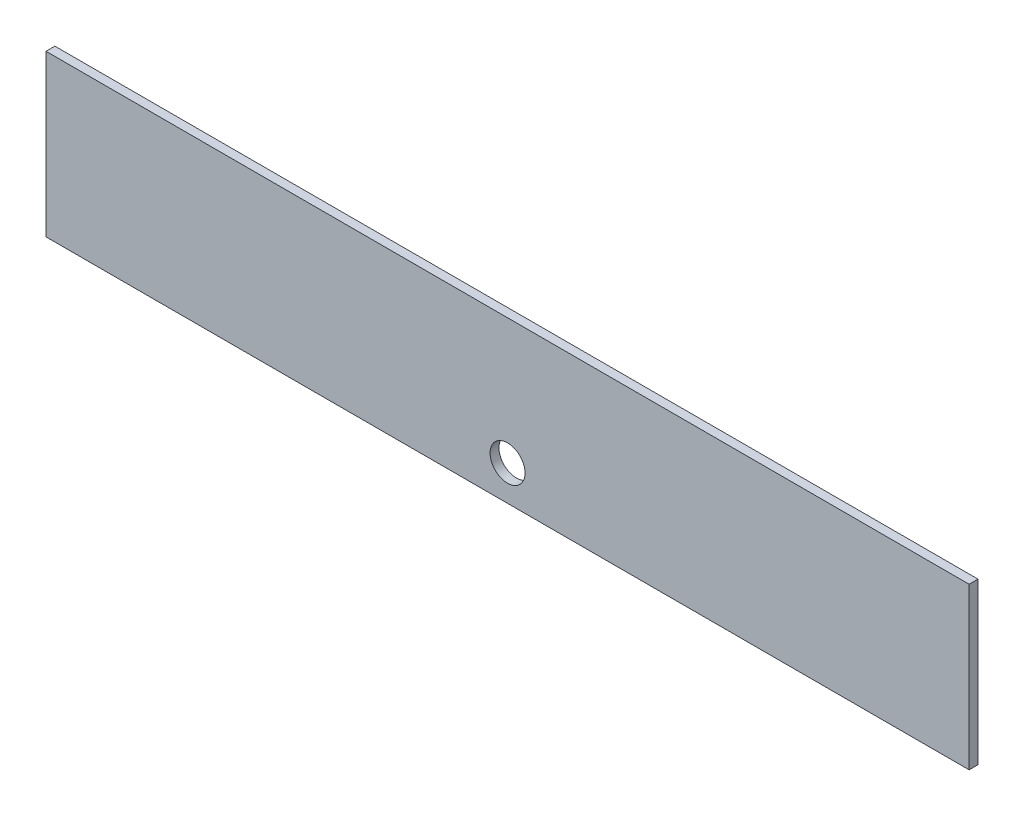
SolidWorks part; units mm, degrees
material "Acrylic (Medium-high impact)"
ref_plane "Front Plane" through (0, 0, 0) normal (0, 0, 1) x (1, 0, 0)
ref_plane "Top Plane" through (0, 0, 0) normal (0, 1, 0) x (1, 0, 0)
ref_plane "Right Plane" through (0, 0, 0) normal (1, 0, 0) x (0, 0, -1)
sketch "Sketch1" plane through (0, 0, 0) normal (0, 0, 1) x (1, 0, 0)
  line L0 (-330.2, -25) -> (330.2, -25)
  line L2 (-330.2, -25) -> (-330.2, 90)
  line L3 (-330.2, 90) -> (330.2, 90)
  line L4 (330.2, -25) -> (330.2, 90)
  point P0 (0, 0)
  point P5 (0, 0)
  dimension "D1" = 660.4
  dimension "D2" = 90
  dimension "D3" = 25
extrude "Boss-Extrude1" add sketch "Sketch1" along normal blind 6.35
sketch "Sketch2" plane through (0, 0, 0) normal (0, 0, -1) x (-1, 0, 0)
  line L0 (330.2, -25) -> (-330.2, -25) construction
  circle A0 centre (0, 0) radius 12.5
  dimension "D1" = 25
  dimension "D2" = 25
extrude "Cut-Extrude1" cut sketch "Sketch2" against normal through all
